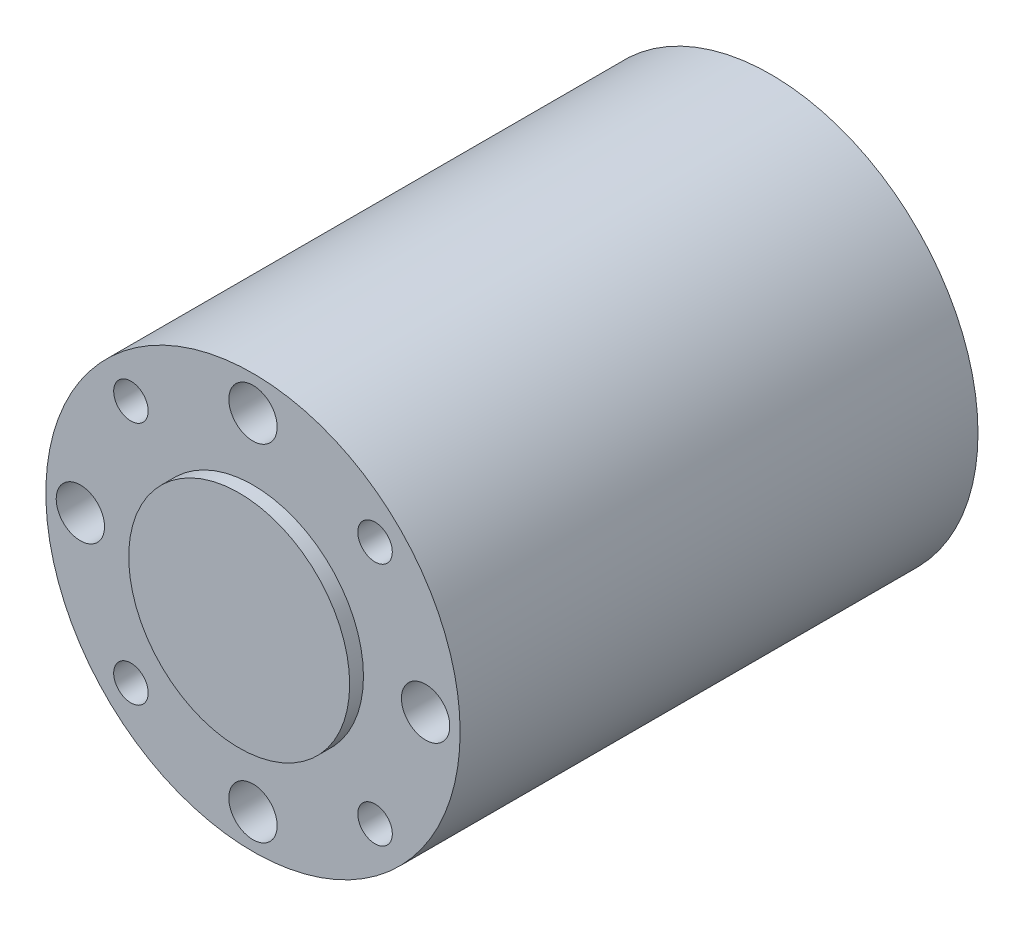
SolidWorks part; units mm, degrees
ref_plane "Front Plane" through (0, 0, 0) normal (0, 0, 1) x (1, 0, 0)
ref_plane "Top Plane" through (0, 0, 0) normal (0, 1, 0) x (1, 0, 0)
ref_plane "Right Plane" through (0, 0, 0) normal (1, 0, 0) x (0, 0, -1)
sketch "Sketch1" plane through (0, 0, 0) normal (0, 0, 1) x (1, 0, 0)
  circle A0 centre (0, 0) radius 30
  dimension "D1" = 60
extrude "Boss-Extrude1" add sketch "Sketch1" along normal blind 75
sketch "Sketch2" plane through (0, 0, 75) normal (0, 0, 1) x (1, 0, 0)
  line L0 (0, 30) -> (0, -30) construction
  line L1 (30, 0) -> (-30, 0) construction
  line L2 (-21.2132, -21.2132) -> (21.2132, 21.2132) construction
  line L3 (21.2132, -21.2132) -> (-21.2132, 21.2132) construction
  circle A0 centre (0, 0) radius 30 construction
  circle A1 centre (0, 25) radius 3.5
  circle A2 centre (17.6777, 17.6777) radius 2.5
  circle A3 centre (-17.6777, 17.6777) radius 2.5
  circle A4 centre (17.6777, -17.6777) radius 2.5
  circle A5 centre (-17.6777, -17.6777) radius 2.5
  circle A6 centre (25, 0) radius 3.5
  circle A7 centre (-25, 0) radius 3.5
  circle A8 centre (0, -25) radius 3.5
  dimension "D3" = 5
  dimension "D5" = 7
  dimension "D1" = 45
  dimension "D2" = 45
  dimension "D4" = 5
  dimension "D6" = 5
extrude "Cut-Extrude1" cut sketch "Sketch2" against normal blind 10
sketch "Sketch3" plane through (0, 0, 75) normal (0, 0, 1) x (1, 0, 0)
  circle A0 centre (0, 0) radius 16
  dimension "D1" = 32
extrude "Boss-Extrude2" add sketch "Sketch3" along normal blind 2
